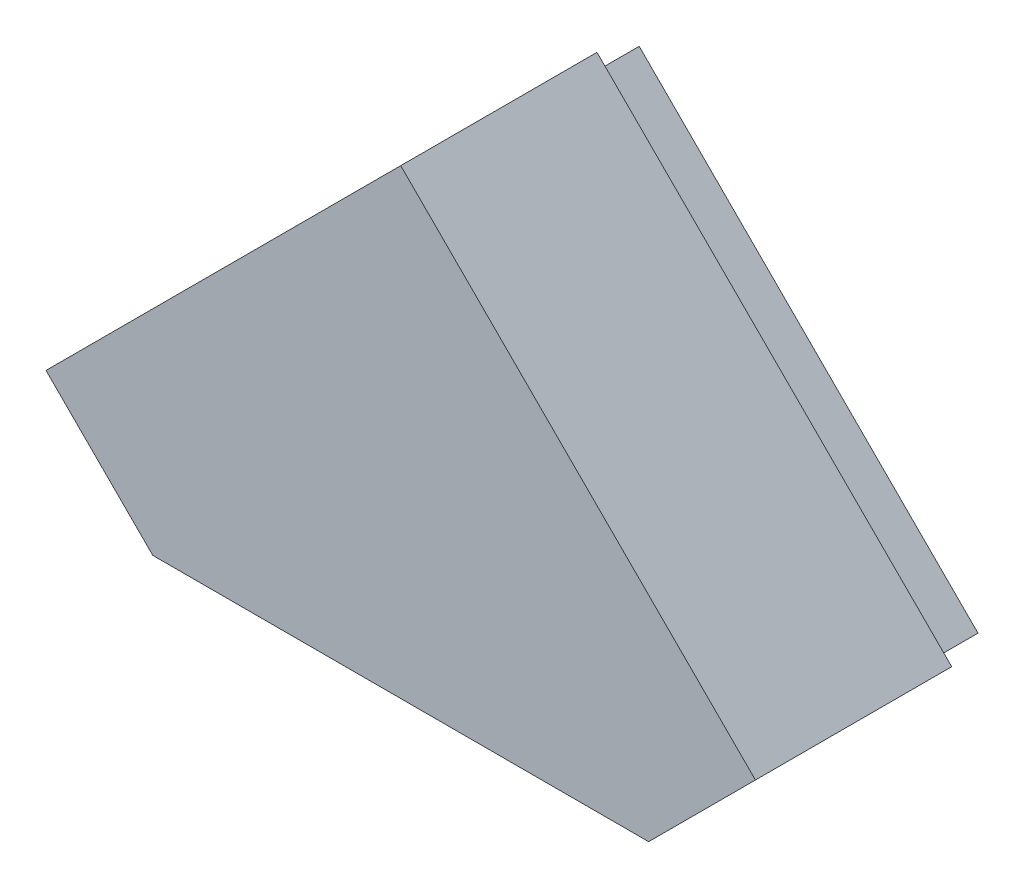
SolidWorks part; units mm, degrees
ref_plane "Спереди" through (0, 0, 0) normal (0, 0, 1) x (1, 0, 0)
ref_plane "Сверху" through (0, 0, 0) normal (0, 1, 0) x (1, 0, 0)
ref_plane "Справа" through (0, 0, 0) normal (1, 0, 0) x (0, 0, -1)
sketch "Эскиз1" plane through (0, 0, 0) normal (0, 0, 1) x (1, 0, 0)
  line L0 (-17, -12) -> (17, -12)
  line L1 (17, -12) -> (23.0901, -5.9099)
  line L2 (23.0901, -5.9099) -> (0, 17.1802)
  line L3 (0, 17.1802) -> (-23.0901, -5.9099)
  line L4 (-23.0901, -5.9099) -> (-17, -12)
  line L5 (16.5, -10.5) -> (-16.5, -10.5) construction
  dimension "D1" = 90
  dimension "D2" = 90
  dimension "D3" = 90
  dimension "D4" = 1.5
  dimension "D5" = 0.5
  dimension "D6" = 0.5
extrude "Вытянуть-Тонкостенный1" add sketch "Эскиз1" along normal blind 12.75 and the other way blind 12.75 thin
sketch "Эскиз2" plane through (0, 0, 12.75) normal (0, 0, 1) x (1, 0, 0)
  line L0 (25.2114, -5.9099) -> (0, 19.3015) construction
  line L1 (17.6213, -13.5) -> (25.2114, -5.9099) construction
  line L2 (-17.6213, -13.5) -> (17.6213, -13.5) construction
  line L3 (-25.2114, -5.9099) -> (-17.6213, -13.5) construction
  line L4 (0, 19.3015) -> (-25.2114, -5.9099) construction
  line L5 (25.2114, -5.9099) -> (0, 19.3015)
  line L6 (17.6213, -13.5) -> (25.2114, -5.9099)
  line L7 (-17.6213, -13.5) -> (17.6213, -13.5)
  line L8 (-25.2114, -5.9099) -> (-17.6213, -13.5)
  line L9 (0, 19.3015) -> (-25.2114, -5.9099)
extrude "Бобышка-Вытянуть1" add sketch "Эскиз2" along normal blind 1.2
sketch "Эскиз3" plane through (0, 0, -12.75) normal (0, 0, -1) x (-1, 0, 0)
  line L0 (0, 19.3015) -> (25.2114, -5.9099) construction
  line L1 (25.2114, -5.9099) -> (17.6213, -13.5) construction
  line L2 (17.6213, -13.5) -> (-17.6213, -13.5) construction
  line L3 (-17.6213, -13.5) -> (-25.2114, -5.9099) construction
  line L4 (-25.2114, -5.9099) -> (0, 19.3015) construction
  line L5 (0, 19.3015) -> (25.2114, -5.9099)
  line L6 (25.2114, -5.9099) -> (17.6213, -13.5)
  line L7 (17.6213, -13.5) -> (-17.6213, -13.5)
  line L8 (-17.6213, -13.5) -> (-25.2114, -5.9099)
  line L9 (-25.2114, -5.9099) -> (0, 19.3015)
extrude "Бобышка-Вытянуть2" add sketch "Эскиз3" along normal blind 1.2
sketch "Эскиз4" plane through (0, -13.5, 0) normal (0, -1, 0) x (1, 0, 0)
  line L0 (11.5, 11.5) -> (-11.5, 11.5) construction
  line L1 (-11.8, 11.8) -> (11.8, 11.8)
  line L2 (-11.8, 11.8) -> (-11.8, -11.8)
  line L3 (-11.8, -11.8) -> (11.8, -11.8)
  line L4 (11.8, 11.8) -> (11.8, -11.8)
  line L5 (-11.8, 11.8) -> (11.8, -11.8) construction
  line L6 (-11.8, -11.8) -> (11.8, 11.8) construction
  line L7 (11.5, -11.5) -> (11.5, 11.5) construction
  point P0 (0, 0)
  dimension "D1" = 0.3
  dimension "D2" = 0.3
extrude "Вырез-Вытянуть1" cut sketch "Эскиз4" against normal up to surface (1.5 mm away) up to face at (0, -12, 0)
sketch "Эскиз5" plane through (0, 0, 0) normal (1, 0, 0) x (0, 0, -1)
  line L0 (13.95, 19.3015) -> (-13.95, 19.3015) construction
  line L1 (0, 19.3015) -> (13.95, 19.3015)
  line L2 (0, 19.3015) -> (0, -13.5)
  line L3 (0, -13.5) -> (13.95, -13.5)
  line L4 (13.95, 19.3015) -> (13.95, -13.5)
extrude "Вырез-Вытянуть2" cut sketch "Эскиз5" against normal through all and the other way through all
sketch "Эскиз7" plane through (0, 0, 0) normal (0, 0, -1) x (-1, 0, 0)
  line L9 (-17.2899, -12.7) -> (-11.8, -12.7)
  line L10 (-24.08, -5.9099) -> (-17.2899, -12.7)
  line L11 (0.5657, 18.7358) -> (-24.08, -5.9099)
  line L12 (-17.2899, -12.7) -> (-11.8, -12.7)
  line L13 (-24.08, -5.9099) -> (-17.2899, -12.7)
  line L14 (0, 18.1701) -> (-24.08, -5.9099)
  line L18 (-11.8, -12.7) -> (-11.8, -12)
  line L19 (-11.8, -12) -> (-17, -12)
  line L20 (-17, -12) -> (-23.0901, -5.9099)
  line L21 (11.8, -12.7) -> (17.2899, -12.7)
  line L22 (17.2899, -12.7) -> (24.08, -5.9099)
  line L23 (24.08, -5.9099) -> (-0.5657, 18.7358)
  line L24 (11.8, -12.7) -> (17.2899, -12.7)
  line L25 (17.2899, -12.7) -> (24.08, -5.9099)
  line L26 (24.08, -5.9099) -> (0, 18.1701)
  line L27 (-23.0901, -5.9099) -> (0, 17.1802)
  line L28 (0, 17.1802) -> (23.0901, -5.9099)
  line L29 (23.0901, -5.9099) -> (17, -12)
  line L30 (17, -12) -> (11.8, -12)
  line L31 (11.8, -12) -> (11.8, -12.7)
  dimension "D1" = 0.8
  dimension "D2" = 0.8
extrude "Бобышка-Вытянуть3" add sketch "Эскиз7" along normal blind 3
